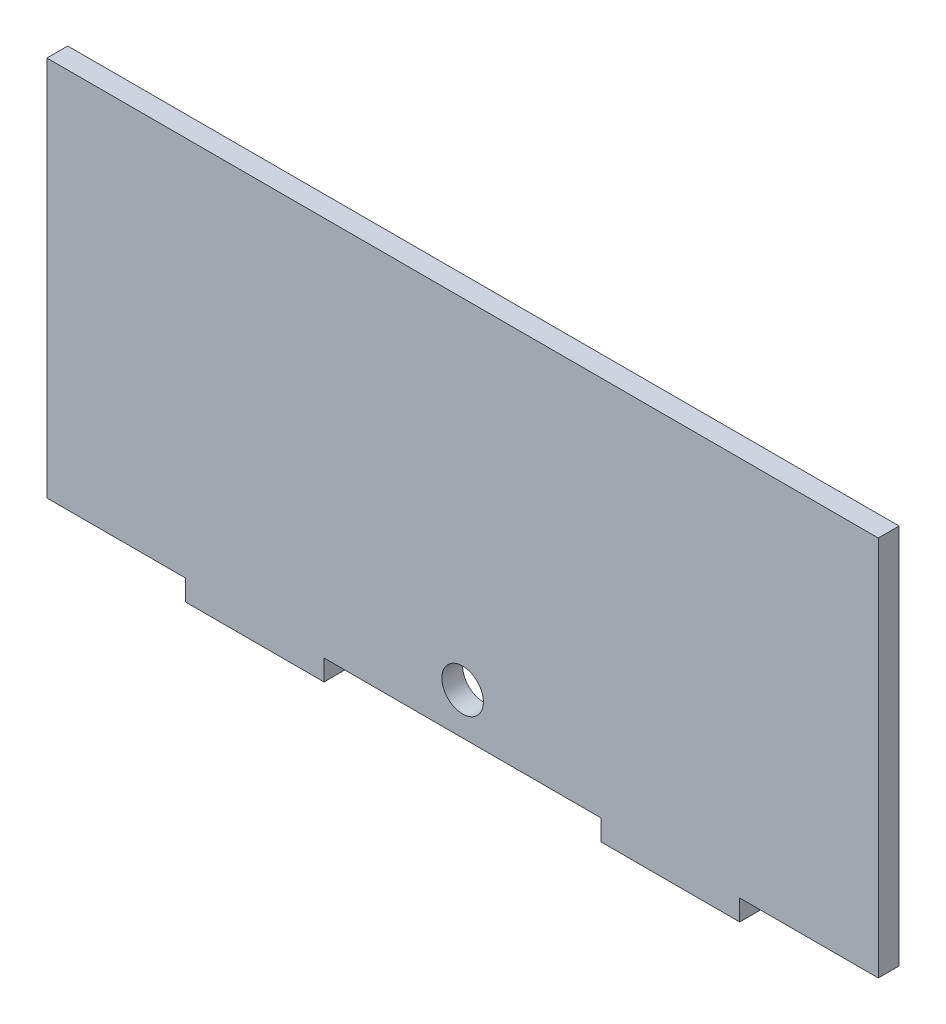
SolidWorks part; units mm, degrees
material "Acrylic (Medium-high impact)"
ref_plane "Front Plane" through (0, 0, 0) normal (0, 0, 1) x (1, 0, 0)
ref_plane "Top Plane" through (0, 0, 0) normal (0, 1, 0) x (1, 0, 0)
ref_plane "Right Plane" through (0, 0, 0) normal (1, 0, 0) x (0, 0, -1)
sketch "Sketch1" plane through (0, 0, 0) normal (0, 0, 1) x (1, 0, 0)
  line L0 (0, 55) -> (120, 0) construction
  line L1 (0, 0) -> (120, 0)
  line L2 (0, 0) -> (0, 55)
  line L3 (0, 55) -> (120, 55)
  line L4 (120, 0) -> (120, 55)
  line L5 (120, 55) -> (0, 0) construction
  line L6 (60, 27.5) -> (60, -25.031) construction
  circle A0 centre (60, 6) radius 3
  dimension "D3" = 6
  dimension "D1" = 55
  dimension "D2" = 120
  dimension "D4" = 6
extrude "Boss-Extrude1" add sketch "Sketch1" against normal blind 3
sketch "Sketch2" plane through (0, 0, 0) normal (0, 0, 1) x (1, 0, 0)
  line L0 (0, 0) -> (120, 0) construction
  line L1 (20, 0) -> (40, 0)
  line L2 (20, 0) -> (20, -3)
  line L3 (20, -3) -> (40, -3)
  line L4 (40, 0) -> (40, -3)
  line L5 (0, 55) -> (0, 0) construction
  line L6 (80, 0) -> (100, 0)
  line L7 (80, 0) -> (80, -3)
  line L8 (80, -3) -> (100, -3)
  line L9 (100, 0) -> (100, -3)
  point P12 (0, 0)
  dimension "D1" = 3
  dimension "D2" = 3
  dimension "D3" = 20
  dimension "D4" = 40
  dimension "D5" = 20
  dimension "D6" = 20
extrude "Boss-Extrude2" add sketch "Sketch2" against normal blind 3
